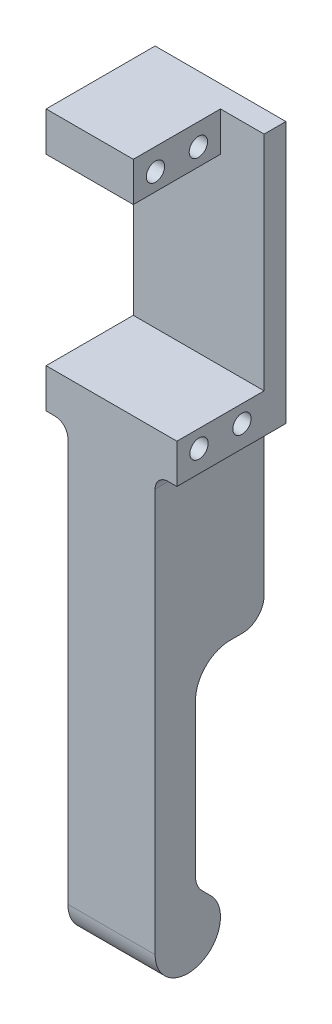
SolidWorks part; units mm, degrees
material "ABS"
ref_plane "前视基准面" through (0, 0, 0) normal (0, 0, 1) x (1, 0, 0)
ref_plane "上视基准面" through (0, 0, 0) normal (0, 1, 0) x (1, 0, 0)
ref_plane "右视基准面" through (0, 0, 0) normal (1, 0, 0) x (0, 0, -1)
other "Configuration Table"
sketch "草图1" plane through (0, 0, 0) normal (0, 0, 1) x (1, 0, 0)
  line L0 (-15, -30) -> (-13, -30)
  line L1 (-15, 30) -> (15, 30)
  line L2 (-15, 30) -> (-15, -30)
  line L7 (0, -133) -> (-10, -133)
  line L8 (-10, -133) -> (-10, -33)
  line L10 (10, -61) -> (10, -133)
  line L11 (10, -133) -> (0, -133)
  line L12 (15, -30) -> (13, -30)
  line L13 (15, 30) -> (15, -30)
  line L14 (10, -33) -> (10, -61)
  arc A0 (-13, -30) -> (-10, -33) centre (-13, -33) cw
  arc A2 (13, -30) -> (10, -33) centre (13, -33) ccw
  point P0 (0, 0)
  dimension "D1" = 3
extrude "凸台-拉伸1" add sketch "草图1" along normal blind 25
sketch "草图2" plane through (0, 0, 25) normal (0, 0, 1) x (1, 0, 0)
  line L23 (-15, 30) -> (-15, -30) construction
  line L24 (-15, -21) -> (15, -21)
  line L25 (15, -30) -> (15, 30) construction
  line L26 (15, -21) -> (15, 30)
  line L27 (15, 30) -> (-15, 30) construction
  line L28 (15, 30) -> (5, 30)
  line L29 (5, 30) -> (5, 21)
  line L30 (5, 21) -> (-15, 21)
  line L31 (-15, 21) -> (-15, -21)
  point P0 (0, 0)
extrude "切除-拉伸1" cut sketch "草图2" against normal blind 20
sketch "草图3" plane through (-15, 0, 0) normal (-1, 0, 0) x (0, 0, 1)
  circle A0 centre (10.075, 25) radius 2.1
  circle A1 centre (19.925, 25) radius 2.1
  circle A2 centre (19.925, -25) radius 2.1
  circle A3 centre (10.075, -25) radius 2.1
extrude "切除-拉伸2" cut sketch "草图3" against normal through all
sketch "草图5" plane through (-10, 0, 0) normal (-1, 0, 0) x (0, 0, 1)
  line L4 (12.1967, -120.1967) -> (14.2678, -118.1256)
  line L11 (5, -71.6612) -> (7.7322, -71.6612)
  line L13 (0, -143.424) -> (25, -142.5922)
  line L14 (25, -142.5922) -> (25, -125.5)
  line L16 (0, -66.6612) -> (0, -143.424)
  line L17 (15.7322, -79.6612) -> (15.7322, -114.5901)
  arc A0 (12.1967, -120.1967) -> (25, -125.5) centre (17.5, -125.5) ccw
  arc A1 (14.2678, -118.1256) -> (15.7322, -114.5901) centre (10.7322, -114.5901) ccw
  arc A3 (5, -71.6612) -> (0, -66.6612) centre (5, -66.6612) cw
  arc A4 (15.7322, -79.6612) -> (7.7322, -71.6612) centre (7.7322, -79.6612) ccw
  dimension "D1" = 5
  dimension "D2" = 5
  dimension "D3" = 8
extrude "切除-拉伸4" cut sketch "草图5" against normal through all
